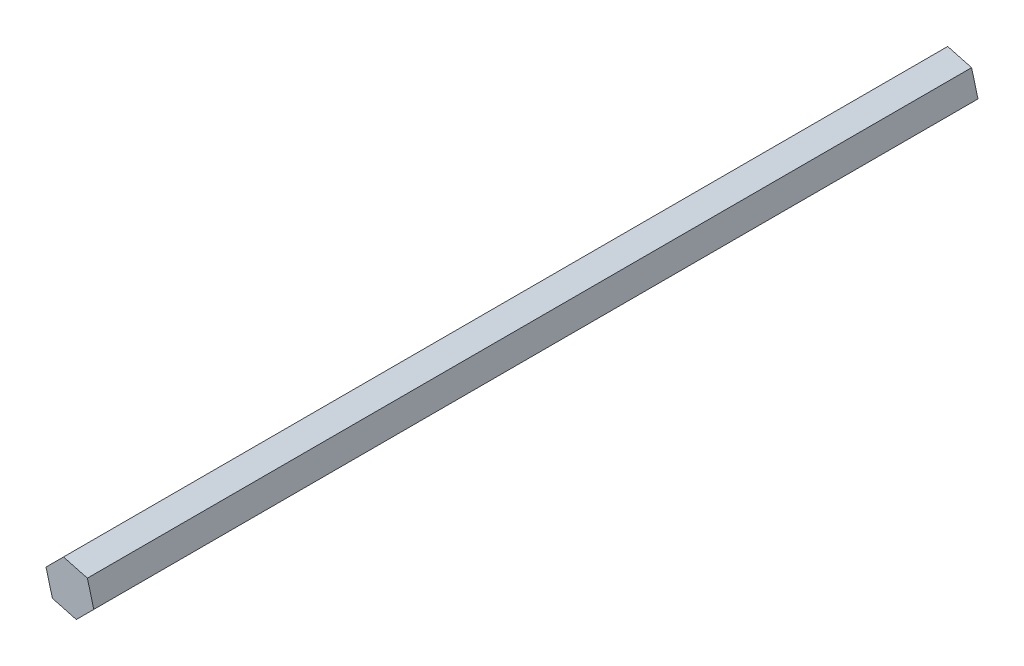
SolidWorks part; units mm, degrees
ref_plane "Front Plane" through (0, 0, 0) normal (0, 0, 1) x (1, 0, 0)
ref_plane "Top Plane" through (0, 0, 0) normal (0, 1, 0) x (1, 0, 0)
ref_plane "Right Plane" through (0, 0, 0) normal (1, 0, 0) x (0, 0, -1)
sketch "Sketch1" plane through (0, 0, 0) normal (0, 0, 1) x (1, 0, 0)
  line L1 (12.7, -3.403) -> (9.297, 9.297)
  line L2 (9.297, 9.297) -> (-3.403, 12.7)
  line L3 (-3.403, 12.7) -> (-12.7, 3.403)
  line L4 (-12.7, 3.403) -> (-9.297, -9.297)
  line L5 (-9.297, -9.297) -> (3.403, -12.7)
  line L6 (3.403, -12.7) -> (12.7, -3.403)
  circle A0 centre (0, 0) radius 11.3865 construction
  dimension "D1" = 12.7
  dimension "D2" = 12.7
extrude "Boss-Extrude1" add sketch "Sketch1" along normal blind 469.9
